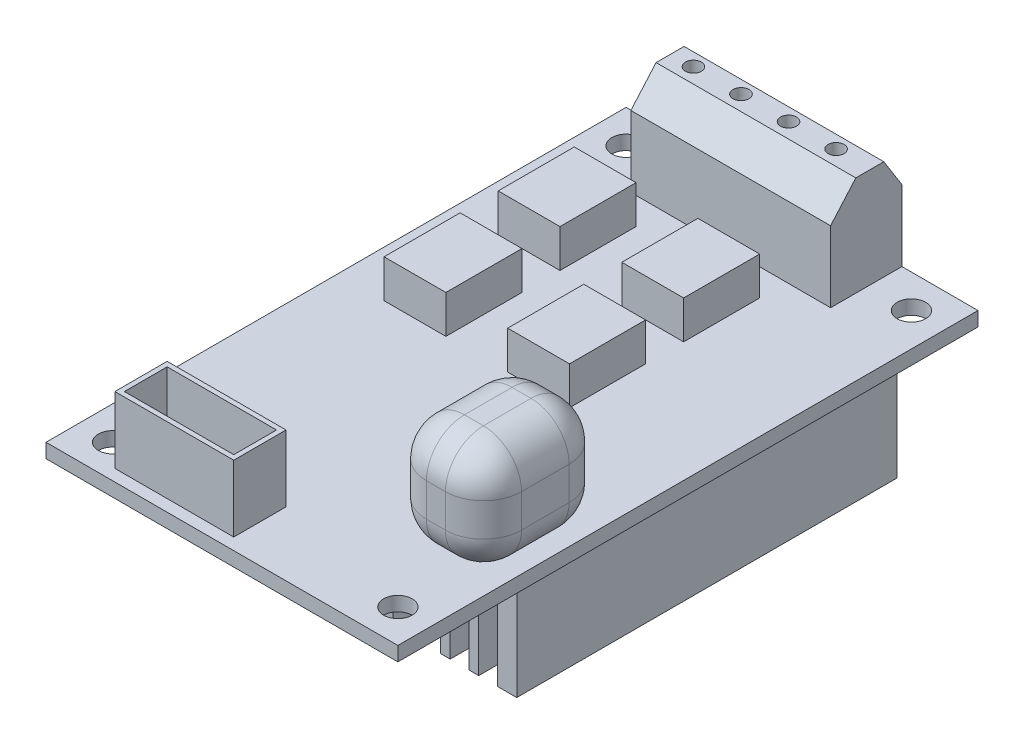
SolidWorks part; units mm, degrees
ref_plane "前视基准面" through (0, 0, 0) normal (0, 0, 1) x (1, 0, 0)
ref_plane "上视基准面" through (0, 0, 0) normal (0, 1, 0) x (1, 0, 0)
ref_plane "右视基准面" through (0, 0, 0) normal (1, 0, 0) x (0, 0, -1)
sketch "草图1" plane through (0, 0, 0) normal (0, 1, 0) x (1, 0, 0)
  line L0 (0, 0) -> (37, 0)
  line L1 (37, 0) -> (37, 61)
  line L2 (37, 61) -> (0, 61)
  line L3 (0, 61) -> (0, 0)
  circle A0 centre (3.5, 57.5) radius 1.5
  circle A1 centre (33.5, 57.5) radius 1.5
  circle A2 centre (3.5, 3.5) radius 1.5
  circle A3 centre (33.5, 3.5) radius 1.5
  dimension "D3" = 3
  dimension "D8" = 3
  dimension "D9" = 3
  dimension "D10" = 3
  dimension "D1" = 61
  dimension "D2" = 37
  dimension "D4" = 3.5
  dimension "D5" = 3.5
  dimension "D6" = 3.5
  dimension "D7" = 3.5
  dimension "D11" = 3.5
  dimension "D12" = 3.5
  dimension "D13" = 3.5
  dimension "D14" = 3.5
extrude "凸台-拉伸1" add sketch "草图1" along normal blind 1.5
sketch "草图2" plane through (0, 0, 0) normal (0, -1, 0) x (1, 0, 0)
  line L0 (36, -53.5) -> (1, -53.5)
  line L1 (1, -53.5) -> (1, -13.5)
  line L2 (1, -13.5) -> (36, -13.5)
  line L3 (36, -13.5) -> (36, -53.5)
  line L4 (37, 0) -> (37, -61) construction
  line L5 (0, -61) -> (0, 0) construction
  line L6 (37, -61) -> (0, -61) construction
  dimension "D1" = 1
  dimension "D2" = 1
  dimension "D3" = 7.5
  dimension "D4" = 40
extrude "凸台-拉伸2" add sketch "草图2" along normal blind 10.5
sketch "草图3" plane through (0, 1.5, 0) normal (0, 1, 0) x (1, 0, 0)
  line L0 (6, 1.24) -> (18.5, 1.24)
  line L1 (18.5, 1.24) -> (18.5, 6.74)
  line L2 (18.5, 6.74) -> (6, 6.74)
  line L3 (6, 6.74) -> (6, 1.24)
  line L4 (0, 61) -> (0, 0) construction
  dimension "D1" = 6
  dimension "D2" = 12.5
  dimension "D3" = 5.5
extrude "凸台-拉伸3" add sketch "草图3" along normal blind 7
sketch "草图4" plane through (0, 1.5, 0) normal (0, 1, 0) x (1, 0, 0)
  line L0 (8, 61) -> (8, 53.5)
  line L1 (37, 61) -> (0, 61) construction
  line L2 (8, 53.5) -> (29, 53.5)
  line L3 (29, 53.5) -> (29, 61)
  line L4 (29, 61) -> (8, 61)
  line L5 (0, 61) -> (0, 0) construction
  line L6 (37, 0) -> (37, 61) construction
  dimension "D1" = 8
  dimension "D2" = 7.5
  dimension "D3" = 8
extrude "凸台-拉伸4" add sketch "草图4" along normal blind 10.5 separate body
sketch "草图5" plane through (0, 1.5, 0) normal (0, 1, 0) x (1, 0, 0)
  line L0 (37, 9) -> (27, 9)
  line L1 (37, 0) -> (37, 61) construction
  line L2 (27, 9) -> (27, 22)
  line L3 (27, 22) -> (37, 22)
  line L4 (37, 22) -> (37, 9)
  line L5 (0, 0) -> (37, 0) construction
  dimension "D1" = 9
  dimension "D2" = 10
  dimension "D3" = 13
extrude "凸台-拉伸5" add sketch "草图5" along normal blind 11.5 separate body
sketch "草图6" plane through (0, 8.5, 0) normal (0, 1, 0) x (1, 0, 0)
  line L0 (6.5, 6.24) -> (6.5, 1.74)
  line L1 (6.5, 1.74) -> (18, 1.74)
  line L2 (18, 1.74) -> (18, 6.24)
  line L3 (18, 6.24) -> (6.5, 6.24)
extrude "切除-拉伸1" cut sketch "草图6" against normal up to surface (7 mm away) up to face at (3.5, 1.5, -2)
sketch "草图8" plane through (8, 0, 0) normal (-1, 0, 0) x (0, 0, 1)
  line L0 (-59.0961, 12) -> (-61, 8.9675)
  line L1 (-61, 12) -> (-53.5, 12) construction
  line L2 (-61, 12) -> (-61, 1.5) construction
  line L3 (-61, 8.9675) -> (-61, 12)
  line L4 (-61, 12) -> (-59.0961, 12)
  line L5 (-56.1496, 12) -> (-53.5, 8.9675)
  line L6 (-53.5, 12) -> (-53.5, 1.5) construction
  line L7 (-53.5, 8.9675) -> (-53.5, 12)
  line L8 (-53.5, 12) -> (-56.1496, 12)
extrude "切除-拉伸3" cut sketch "草图8" against normal up to next (21 mm away)
sketch "草图9" plane through (0, 12, 0) normal (0, 1, 0) x (1, 0, 0)
  circle A0 centre (25.3361, 57.7416) radius 0.8412
  circle A1 centre (20.3361, 57.7416) radius 0.8412
  circle A2 centre (15.3361, 57.7416) radius 0.8412
  circle A3 centre (10.3361, 57.7416) radius 0.8412
  dimension "D1" = 4
extrude "切除-拉伸4" cut sketch "草图9" against normal blind 3
fillet "圆角2" radius 4 12 edges at (32, 1.5, -22) (32, 1.5, -9) (27, 7.25, -22) (27, 7.25, -9) (27, 1.5, -15.5) (32, 13, -9) (27, 13, -15.5) (32, 13, -22) (37, 7.25, -9) (37, 13, -15.5) (37, 7.25, -22) (37, 1.5, -15.5)
sketch "草图10" plane through (0, 1.5, 0) normal (0, 1, 0) x (1, 0, 0)
  line L0 (4.8809, 50.6655) -> (11.3809, 50.6655)
  line L1 (11.3809, 50.6655) -> (11.3809, 42.6655)
  line L2 (11.3809, 42.6655) -> (4.8809, 42.6655)
  line L3 (4.8809, 42.6655) -> (4.8809, 50.6655)
  line L4 (4.8809, 30.6655) -> (4.8809, 38.6655)
  line L5 (4.8809, 38.6655) -> (11.3809, 38.6655)
  line L6 (11.3809, 38.6655) -> (11.3809, 30.6655)
  line L7 (11.3809, 30.6655) -> (4.8809, 30.6655)
  line L8 (17.8809, 30.6655) -> (17.8809, 38.6655)
  line L9 (17.8809, 38.6655) -> (24.3809, 38.6655)
  line L10 (24.3809, 38.6655) -> (24.3809, 30.6655)
  line L11 (24.3809, 30.6655) -> (17.8809, 30.6655)
  line L12 (17.8809, 42.6655) -> (17.8809, 50.6655)
  line L13 (17.8809, 50.6655) -> (24.3809, 50.6655)
  line L14 (24.3809, 50.6655) -> (24.3809, 42.6655)
  line L15 (24.3809, 42.6655) -> (17.8809, 42.6655)
  dimension "D1" = 8
  dimension "D2" = 6.5
  dimension "D3" = 2
  dimension "D4" = 2
extrude "凸台-拉伸6" add sketch "草图10" along normal blind 4
sketch "草图11" plane through (0, 0, -53.5) normal (0, 0, -1) x (-1, 0, 0)
  line L0 (-34, -10.5) -> (-34, -0.5)
  line L1 (-1, -10.5) -> (-36, -10.5) construction
  line L2 (-34, -0.5) -> (-32, -0.5)
  line L3 (-32, -0.5) -> (-32, -10.5)
  line L4 (-32, -10.5) -> (-34, -10.5)
  line L5 (-36, -10.5) -> (-36, 0) construction
  line L6 (-29, -10.5) -> (-31, -10.5)
  line L7 (-31, -10.5) -> (-31, -0.5)
  line L8 (-31, -0.5) -> (-29, -0.5)
  line L9 (-29, -0.5) -> (-29, -10.5)
  line L10 (-26, -10.5) -> (-28, -10.5)
  line L11 (-28, -10.5) -> (-28, -0.5)
  line L12 (-28, -0.5) -> (-26, -0.5)
  line L13 (-26, -0.5) -> (-26, -10.5)
  line L14 (-23, -10.5) -> (-25, -10.5)
  line L15 (-25, -10.5) -> (-25, -0.5)
  line L16 (-25, -0.5) -> (-23, -0.5)
  line L17 (-23, -0.5) -> (-23, -10.5)
  line L18 (-20, -10.5) -> (-22, -10.5)
  line L19 (-22, -10.5) -> (-22, -0.5)
  line L20 (-22, -0.5) -> (-20, -0.5)
  line L21 (-20, -0.5) -> (-20, -10.5)
  line L22 (-17, -10.5) -> (-19, -10.5)
  line L23 (-19, -10.5) -> (-19, -0.5)
  line L24 (-19, -0.5) -> (-17, -0.5)
  line L25 (-17, -0.5) -> (-17, -10.5)
  line L26 (-14, -10.5) -> (-16, -10.5)
  line L27 (-16, -10.5) -> (-16, -0.5)
  line L28 (-16, -0.5) -> (-14, -0.5)
  line L29 (-14, -0.5) -> (-14, -10.5)
  line L30 (-11, -10.5) -> (-13, -10.5)
  line L31 (-13, -10.5) -> (-13, -0.5)
  line L32 (-13, -0.5) -> (-11, -0.5)
  line L33 (-11, -0.5) -> (-11, -10.5)
  line L34 (-8, -10.5) -> (-10, -10.5)
  line L35 (-10, -10.5) -> (-10, -0.5)
  line L36 (-10, -0.5) -> (-8, -0.5)
  line L37 (-8, -0.5) -> (-8, -10.5)
  dimension "D1" = 2
  dimension "D2" = 2
  dimension "D3" = 10
  dimension "D4" = 9
extrude "切除-拉伸5" cut sketch "草图11" against normal through all
